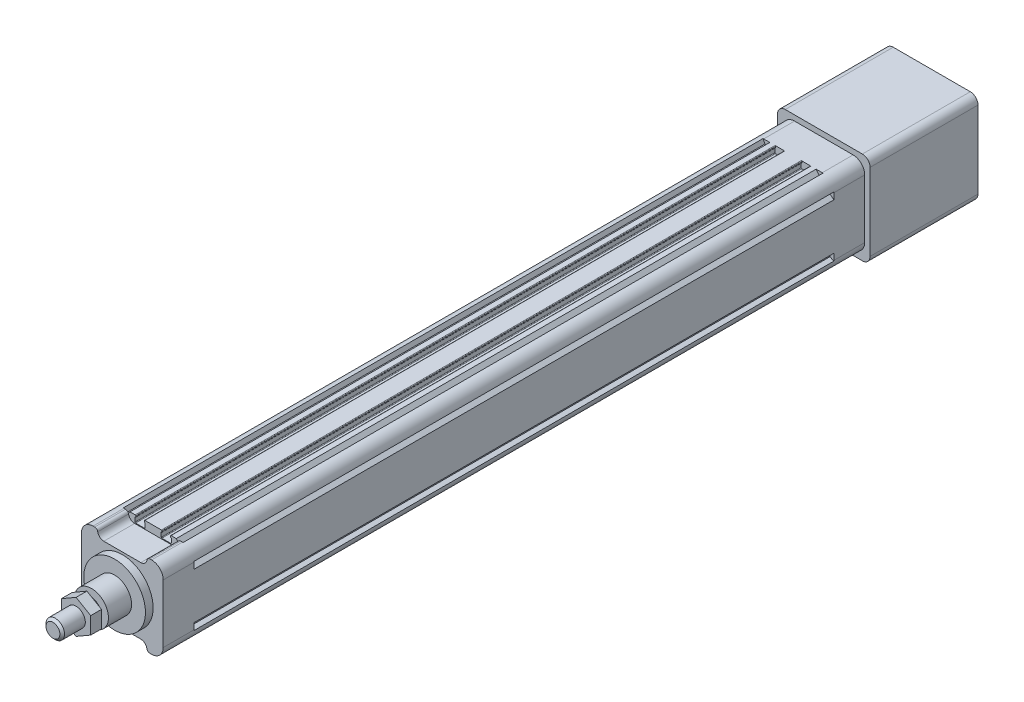
SolidWorks part; units mm, degrees
ref_plane "Front" through (0, 0, 0) normal (0, 0, 1) x (1, 0, 0)
ref_plane "Top" through (0, 0, 0) normal (0, 1, 0) x (1, 0, 0)
ref_plane "Right" through (0, 0, 0) normal (1, 0, 0) x (0, 0, -1)
sketch "草图1" plane through (0, 0, 0) normal (0, 0, 1) x (1, 0, 0)
  line L0 (19.7737, 3) -> (23.3, 3)
  line L1 (23.3, 3) -> (23.3, -3)
  line L2 (23.3, -3) -> (19.7737, -3)
  line L3 (-19.7737, -3) -> (-23.3, -3)
  line L4 (-23.3, -3) -> (-23.3, 3)
  line L5 (-23.3, 3) -> (-19.7737, 3)
  line L6 (-18.2, 24) -> (-19.4434, 26.4869)
  line L7 (-26.4869, 19.4434) -> (-24, 18.2)
  line L8 (-24, 18.2) -> (-24, 17.1)
  line L9 (-24, 17.1) -> (-26.5, 15)
  line L10 (-26.5, 15) -> (-26.5, -15)
  line L11 (-26.5, -15) -> (-24, -17.1)
  line L12 (-24, -17.1) -> (-24, -18.2)
  line L13 (-24, -18.2) -> (-26.4869, -19.4434)
  line L14 (-19.4434, -26.4869) -> (-18.2, -24)
  line L15 (-18.2, -24) -> (-17.1, -24)
  line L16 (-17.1, -24) -> (-15, -26.5)
  line L17 (-15, -26.5) -> (-11.65, -26.5)
  line L18 (-11.25, -26.1) -> (-11.25, -25.6)
  line L19 (-11.65, -25.2) -> (-11.75, -25.2)
  line L20 (-11.75, -25.2) -> (-11.75, -22.4)
  line L21 (-11.35, -22) -> (-5.65, -22)
  line L22 (-5.25, -22.4) -> (-5.25, -25.2)
  line L23 (-5.25, -25.2) -> (-5.35, -25.2)
  line L24 (-5.75, -25.6) -> (-5.75, -26.1)
  line L25 (-5.35, -26.5) -> (5.35, -26.5)
  line L26 (5.75, -26.1) -> (5.75, -25.6)
  line L27 (5.35, -25.2) -> (5.25, -25.2)
  line L28 (5.25, -25.2) -> (5.25, -22.4)
  line L29 (5.65, -22) -> (11.35, -22)
  line L30 (11.75, -22.4) -> (11.75, -25.2)
  line L31 (11.75, -25.2) -> (11.65, -25.2)
  line L32 (11.25, -25.6) -> (11.25, -26.1)
  line L33 (11.65, -26.5) -> (15, -26.5)
  line L34 (15, -26.5) -> (17.1, -24)
  line L35 (17.1, -24) -> (18.2, -24)
  line L36 (18.2, -24) -> (19.4434, -26.4869)
  line L37 (26.4869, -19.4434) -> (24, -18.2)
  line L38 (24, -18.2) -> (24, -17.1)
  line L39 (24, -17.1) -> (26.5, -15)
  line L40 (26.5, -15) -> (26.5, 15)
  line L41 (26.5, 15) -> (24, 17.1)
  line L42 (24, 17.1) -> (24, 18.2)
  line L43 (24, 18.2) -> (26.4869, 19.4434)
  line L44 (19.4434, 26.4869) -> (18.2, 24)
  line L45 (18.2, 24) -> (17.1, 24)
  line L46 (17.1, 24) -> (15, 26.5)
  line L47 (15, 26.5) -> (11.65, 26.5)
  line L48 (11.25, 26.1) -> (11.25, 25.6)
  line L49 (11.65, 25.2) -> (11.75, 25.2)
  line L50 (11.75, 25.2) -> (11.75, 22.4)
  line L51 (11.35, 22) -> (5.65, 22)
  line L52 (5.25, 22.4) -> (5.25, 25.2)
  line L53 (5.25, 25.2) -> (5.35, 25.2)
  line L54 (5.75, 25.6) -> (5.75, 26.1)
  line L55 (5.35, 26.5) -> (-5.35, 26.5)
  line L56 (-5.75, 26.1) -> (-5.75, 25.6)
  line L57 (-5.35, 25.2) -> (-5.25, 25.2)
  line L58 (-5.25, 25.2) -> (-5.25, 22.4)
  line L59 (-5.65, 22) -> (-11.35, 22)
  line L60 (-11.75, 22.4) -> (-11.75, 25.2)
  line L61 (-11.75, 25.2) -> (-11.65, 25.2)
  line L62 (-11.25, 25.6) -> (-11.25, 26.1)
  line L63 (-11.65, 26.5) -> (-15, 26.5)
  line L64 (-15, 26.5) -> (-17.1, 24)
  line L65 (-17.1, 24) -> (-18.2, 24)
  arc A0 (19.7737, 3) -> (-19.7737, 3) centre (0, 0) ccw
  arc A1 (-19.7737, -3) -> (19.7737, -3) centre (0, 0) ccw
  circle A2 centre (19, 19) radius 2.1
  circle A3 centre (19, -19) radius 2.1
  circle A4 centre (-19, -19) radius 2.1
  circle A5 centre (-19, 19) radius 2.1
  arc A6 (-19.4434, 26.4869) -> (-26.4869, 19.4434) centre (-19, 19) ccw
  arc A7 (-26.4869, -19.4434) -> (-19.4434, -26.4869) centre (-19, -19) ccw
  arc A8 (-11.65, -26.5) -> (-11.25, -26.1) centre (-11.65, -26.1) ccw
  arc A9 (-11.25, -25.6) -> (-11.65, -25.2) centre (-11.65, -25.6) ccw
  arc A10 (-11.35, -22) -> (-11.75, -22.4) centre (-11.35, -22.4) ccw
  arc A11 (-5.25, -22.4) -> (-5.65, -22) centre (-5.65, -22.4) ccw
  arc A12 (-5.35, -25.2) -> (-5.75, -25.6) centre (-5.35, -25.6) ccw
  arc A13 (-5.75, -26.1) -> (-5.35, -26.5) centre (-5.35, -26.1) ccw
  arc A14 (5.35, -26.5) -> (5.75, -26.1) centre (5.35, -26.1) ccw
  arc A15 (5.75, -25.6) -> (5.35, -25.2) centre (5.35, -25.6) ccw
  arc A16 (5.65, -22) -> (5.25, -22.4) centre (5.65, -22.4) ccw
  arc A17 (11.75, -22.4) -> (11.35, -22) centre (11.35, -22.4) ccw
  arc A18 (11.65, -25.2) -> (11.25, -25.6) centre (11.65, -25.6) ccw
  arc A19 (11.25, -26.1) -> (11.65, -26.5) centre (11.65, -26.1) ccw
  arc A20 (19.4434, -26.4869) -> (26.4869, -19.4434) centre (19, -19) ccw
  arc A21 (26.4869, 19.4434) -> (19.4434, 26.4869) centre (19, 19) ccw
  arc A22 (11.65, 26.5) -> (11.25, 26.1) centre (11.65, 26.1) ccw
  arc A23 (11.25, 25.6) -> (11.65, 25.2) centre (11.65, 25.6) ccw
  arc A24 (11.35, 22) -> (11.75, 22.4) centre (11.35, 22.4) ccw
  arc A25 (5.25, 22.4) -> (5.65, 22) centre (5.65, 22.4) ccw
  arc A26 (5.35, 25.2) -> (5.75, 25.6) centre (5.35, 25.6) ccw
  arc A27 (5.75, 26.1) -> (5.35, 26.5) centre (5.35, 26.1) ccw
  arc A28 (-5.35, 26.5) -> (-5.75, 26.1) centre (-5.35, 26.1) ccw
  arc A29 (-5.75, 25.6) -> (-5.35, 25.2) centre (-5.35, 25.6) ccw
  arc A30 (-5.65, 22) -> (-5.25, 22.4) centre (-5.65, 22.4) ccw
  arc A31 (-11.75, 22.4) -> (-11.35, 22) centre (-11.35, 22.4) ccw
  arc A32 (-11.65, 25.2) -> (-11.25, 25.6) centre (-11.65, 25.6) ccw
  arc A33 (-11.25, 26.1) -> (-11.65, 26.5) centre (-11.65, 26.1) ccw
extrude "凸台-拉伸1" add sketch "草图1" along normal blind 415
sketch "草图6" plane through (0, 0, 415) normal (0, 0, 1) x (1, 0, 0)
  line L0 (0, 0) -> (19, 0) construction
  line L2 (-26.5, -19) -> (-26.5, 19)
  line L3 (-19, 26.5) -> (-17.9161, 26.5)
  line L4 (26.5, -19) -> (26.5, 19)
  line L5 (-26.5, -26.5) -> (26.5, 26.5) construction
  line L6 (-26.5, 26.5) -> (26.5, -26.5) construction
  line L7 (-12, 21.5) -> (12, 21.5)
  line L9 (19, 26.5) -> (17.9161, 26.5)
  line L10 (19, -26.5) -> (17.9161, -26.5)
  line L11 (-12, -21.5) -> (12, -21.5)
  line L12 (-19, -26.5) -> (-17.9161, -26.5)
  arc A0 (12, 21.5) -> (15.9441, 24.8333) centre (12, 25.5) ccw
  arc A1 (-15.9441, 24.8333) -> (-12, 21.5) centre (-12, 25.5) ccw
  arc A2 (-15.9441, 24.8333) -> (-17.9161, 26.5) centre (-17.9161, 24.5) ccw
  arc A3 (15.9441, 24.8333) -> (17.9161, 26.5) centre (17.9161, 24.5) cw
  arc A4 (-26.5, -19) -> (-19, -26.5) centre (-19, -19) ccw
  arc A5 (19, -26.5) -> (26.5, -19) centre (19, -19) ccw
  arc A6 (26.5, 19) -> (19, 26.5) centre (19, 19) ccw
  arc A7 (-26.5, 19) -> (-19, 26.5) centre (-19, 19) cw
  arc A8 (15.9441, -24.8333) -> (17.9161, -26.5) centre (17.9161, -24.5) ccw
  arc A9 (12, -21.5) -> (15.9441, -24.8333) centre (12, -25.5) cw
  arc A10 (-15.9441, -24.8333) -> (-12, -21.5) centre (-12, -25.5) cw
  arc A11 (-15.9441, -24.8333) -> (-17.9161, -26.5) centre (-17.9161, -24.5) cw
  point P0 (0, 0)
  point P9 (0, 21.5)
  point P13 (20, 20.8461)
  point P16 (-12, 20.8461)
  dimension "D5" = 4
  dimension "D6" = 2
  dimension "D7" = 2
  dimension "D9" = 7.5
  dimension "D1" = 53
  dimension "D2" = 53
  dimension "D3" = 26.5
  dimension "D4" = 24
  dimension "D8" = 5
extrude "凸台-拉伸2" add sketch "草图6" along normal blind 20
sketch "草图7" plane through (0, 0, 435) normal (0, 0, 1) x (1, 0, 0)
  circle A0 centre (0, 0) radius 20
  dimension "D1" = 40
extrude "凸台-拉伸3" add sketch "草图7" along normal blind 5
sketch "草图9" plane through (0, 0, 440) normal (0, 0, 1) x (1, 0, 0)
  circle A0 centre (0, 0) radius 11
  dimension "D1" = 22
extrude "凸台-拉伸4" add sketch "草图9" along normal blind 15
sketch "草图10" plane through (0, 0, 455) normal (0, 0, 1) x (1, 0, 0)
  circle A0 centre (0, 0) radius 6
  dimension "D1" = 12
extrude "凸台-拉伸5" add sketch "草图10" along normal blind 25
sketch "草图11" plane through (0, 0, 0) normal (0, 0, -1) x (-1, 0, 0)
  line L1 (-19, -26.5) -> (19, -26.5)
  line L2 (-26.5, -19) -> (-26.5, 19)
  line L3 (-19, 26.5) -> (19, 26.5)
  line L4 (26.5, -19) -> (26.5, 19)
  line L5 (-26.5, -26.5) -> (26.5, 26.5) construction
  line L6 (-26.5, 26.5) -> (26.5, -26.5) construction
  arc A0 (-26.5, -19) -> (-19, -26.5) centre (-19, -19) ccw
  arc A1 (19, -26.5) -> (26.5, -19) centre (19, -19) ccw
  arc A2 (26.5, 19) -> (19, 26.5) centre (19, 19) ccw
  arc A3 (-26.5, 19) -> (-19, 26.5) centre (-19, 19) cw
  point P0 (0, 0)
  dimension "D3" = 7.5
  dimension "D1" = 53
  dimension "D2" = 53
extrude "凸台-拉伸6" add sketch "草图11" along normal blind 20
sketch "草图12" plane through (0, 0, -20) normal (0, 0, -1) x (-1, 0, 0)
  line L1 (-25, -30) -> (25, -30)
  line L2 (-30, -25) -> (-30, 25)
  line L3 (-25, 30) -> (25, 30)
  line L4 (30, -25) -> (30, 25)
  line L5 (-30, -30) -> (30, 30) construction
  line L6 (-30, 30) -> (30, -30) construction
  arc A0 (-30, -25) -> (-25, -30) centre (-25, -25) ccw
  arc A1 (25, -30) -> (30, -25) centre (25, -25) ccw
  arc A2 (30, 25) -> (25, 30) centre (25, 25) ccw
  arc A3 (-30, 25) -> (-25, 30) centre (-25, 25) cw
  point P0 (0, 0)
  dimension "D3" = 5
  dimension "D1" = 60
  dimension "D2" = 60
extrude "凸台-拉伸7" add sketch "草图12" along normal blind 70
sketch "草图14" plane through (0, 0, -90) normal (0, 0, -1) x (-1, 0, 0)
  circle A0 centre (0, 0) radius 19
  dimension "D1" = 38
extrude "切除-拉伸2" cut sketch "草图14" against normal blind 70
hole_wizard "M6 螺纹孔1" positions "草图15" profile "草图16" tap size "M6" standard "GB"
sketch "草图15" plane through (-26.5, 0, 0) normal (-1, 0, 0) x (0, 0, 1)
  line L0 (-20, -25) -> (-20, 25) construction
  line L1 (435, 19) -> (435, -19) construction
  point P0 (425, 11)
  point P2 (425, -11)
  point P4 (-10, 11)
  point P6 (-10, -11)
  dimension "D1" = 10
  dimension "D2" = 10
  dimension "D3" = 11
  dimension "D4" = 11
  dimension "D5" = 10
  dimension "D6" = 10
  dimension "D7" = 22
  dimension "D8" = 11
sketch "草图16" plane through (-26.5, 11, 425) normal (0, 1, 0) x (0, 0, 1)
  line L0 (0, 0) -> (0, 16.5022)
  line L1 (0, 16.5022) -> (2.5, 15)
  line L2 (2.5, 15) -> (2.5, 0)
  line L5 (2.5, 0) -> (0, 0)
  line L10 (0, 16.5022) -> (-2.5, 15) construction
  line L11 (0, -6.35) -> (0, 107.95) construction
  dimension "螺纹孔钻头直径" = 5
  dimension "螺纹孔钻头深度" = 15
  dimension "导头角度" = 118
cosmetic thread "孔螺蚊线4" parameters "D1"=12, "D2"=6
cosmetic thread "孔螺蚊线5" parameters "D1"=12, "D2"=6
cosmetic thread "孔螺蚊线6" parameters "D1"=12, "D2"=6
cosmetic thread "孔螺蚊线7" parameters "D1"=12, "D2"=6
chamfer "倒角1" distance 1.5 angle 45 1 edges at (6, 0, 480)
sketch "草图17" plane through (0, 0, 455) normal (0, 0, 1) x (1, 0, 0)
  line L1 (0, 10.9697) -> (-9.5, 5.4848)
  line L2 (-9.5, 5.4848) -> (-9.5, -5.4848)
  line L3 (-9.5, -5.4848) -> (0, -10.9697)
  line L4 (0, -10.9697) -> (9.5, -5.4848)
  line L5 (9.5, -5.4848) -> (9.5, 5.4848)
  line L6 (9.5, 5.4848) -> (0, 10.9697)
  circle A0 centre (0, 0) radius 9.5 construction
  dimension "D1" = 19
extrude "凸台-拉伸8" add sketch "草图17" along normal blind 7 from offset 3
